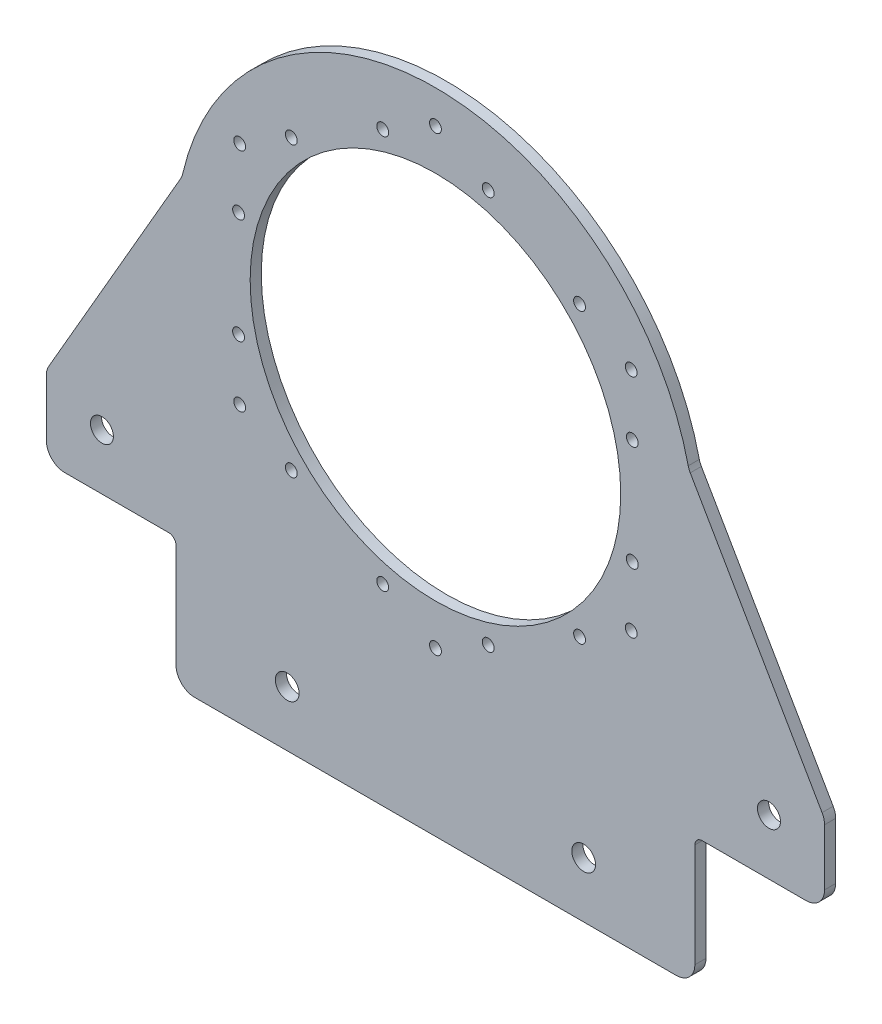
SolidWorks part; units mm, degrees
ref_plane "Front Plane" through (0, 0, 0) normal (0, 0, 1) x (1, 0, 0)
ref_plane "Top Plane" through (0, 0, 0) normal (0, 1, 0) x (1, 0, 0)
ref_plane "Right Plane" through (0, 0, 0) normal (1, 0, 0) x (0, 0, -1)
sketch "Sketch1" plane through (0, 0, 0) normal (0, 0, 1) x (1, 0, 0)
  line L0 (-70, 0) -> (-70, -70)
  line L2 (70, -70) -> (70, 0)
  line L7 (-70, -70) -> (70, -70)
  circle A0 centre (0, 0) radius 50
  arc A1 (70, 0) -> (-70, 0) centre (0, 0) ccw
  arc A2 (-70, 0) -> (0, -70) centre (0, 0) ccw construction
  arc A3 (0, -70) -> (70, 0) centre (0, 0) ccw construction
  dimension "D1" = 140
  dimension "D2" = 100
extrude "Boss-Extrude1" add sketch "Sketch1" along normal blind 3
sketch "Sketch2" plane through (0, 0, 3) normal (0, 0, 1) x (1, 0, 0)
  line L0 (0, 0) -> (0, 61) construction
  circle A0 centre (0, 61) radius 1.6
  circle A1 centre (52.8275, 30.5) radius 1.6
  circle A2 centre (52.8275, -30.5) radius 1.6
  circle A3 centre (0, -61) radius 1.6
  circle A4 centre (-52.8275, -30.5) radius 1.6
  circle A5 centre (-52.8275, 30.5) radius 1.6
  point P16 (0, 0)
  dimension "D1" = 3.2
  dimension "D2" = 61
  dimension "D3" = 6
extrude "Cut-Extrude1" cut sketch "Sketch2" against normal through all
sketch "Sketch3" plane through (0, 0, 3) normal (0, 0, 1) x (1, 0, 0)
  line L0 (0, 0) -> (14.235, 53.1259) construction
  line L1 (0, 0) -> (0, 26.2737) construction
  circle A0 centre (14.235, 53.1259) radius 1.6
  circle A1 centre (38.8909, 38.8909) radius 1.6
  circle A2 centre (53.1259, 14.235) radius 1.6
  circle A3 centre (53.1259, -14.235) radius 1.6
  circle A4 centre (38.8909, -38.8909) radius 1.6
  circle A5 centre (14.235, -53.1259) radius 1.6
  circle A6 centre (-14.235, -53.1259) radius 1.6
  circle A7 centre (-38.8909, -38.8909) radius 1.6
  circle A8 centre (-53.1259, -14.235) radius 1.6
  circle A9 centre (-53.1259, 14.235) radius 1.6
  circle A10 centre (-38.8909, 38.8909) radius 1.6
  circle A11 centre (-14.235, 53.1259) radius 1.6
  point P29 (0, 0)
  dimension "D1" = 3.2
  dimension "D2" = 55
  dimension "D3" = 15
  dimension "D4" = 12
extrude "Cut-Extrude2" cut sketch "Sketch3" against normal through all
sketch "Sketch4" plane through (0, 0, 3) normal (0, 0, 1) x (1, 0, 0)
  line L0 (-68.374, 15) -> (-105, -48.4381)
  line L1 (-105, -48.4381) -> (-105, -70)
  line L2 (-105, -70) -> (-70, -70)
  line L5 (0, 0) -> (0, -70) construction
  line L6 (-70, -70) -> (70, -70) construction
  line L8 (-70, -70) -> (-70, 0)
  line L9 (-90, -70) -> (-90, -55) construction
  line L10 (-40, -90) -> (40, -90) construction
  line L15 (-70, -70) -> (70, -70)
  line L16 (-70, -70) -> (-70, -105)
  line L17 (-70, -105) -> (70, -105)
  line L18 (70, -70) -> (70, -105)
  line L19 (105, -70) -> (70, -70)
  line L20 (105, -48.4381) -> (105, -70)
  line L21 (68.374, 15) -> (105, -48.4381)
  line L22 (70, -70) -> (70, 0)
  circle A0 centre (-40, -90) radius 3.2
  circle A1 centre (-90, -55) radius 3.1
  circle A2 centre (90, -55) radius 3.1
  circle A3 centre (40, -90) radius 3.2
  arc A4 (70, 0) -> (-70, 0) centre (0, 0) ccw construction
  arc A5 (70, 0) -> (68.374, 15) centre (0, 0) ccw
  arc A6 (-68.374, 15) -> (-70, 0) centre (0, 0) ccw
  arc A7 (68.374, 15) -> (70, 0) centre (0, 0) cw
  point P26 (0, -90)
  point P30 (-70, 11.9755)
  point P31 (-68.7758, 13.0342)
  point P32 (-70, 0)
  dimension "D4" = 6.2
  dimension "D5" = 6.4
  dimension "D1" = 30
  dimension "D2" = 35
  dimension "D3" = 15
  dimension "D6" = 80
  dimension "D7" = 15
  dimension "D8" = 35
  dimension "D9" = 15
  dimension "D10" = 15
extrude "Boss-Extrude2" add sketch "Sketch4" against normal up to surface (3 mm away)
chamfer "Chamfer1" [suppressed] distance 2.5 angle 45
thread "Thread1" [suppressed] pitch 0.7 start angle 0, offset 1, length 10, pitch 0.7, diameter 3.2
ref_plane "Plane1" through (-54.4275, -30.5, 4) normal (0, -1, 0) x (-1, 0, 0)
sketch "Thread Profile1" plane through (-54.4275, -30.5, 4) normal (0, -1, 0) x (-1, 0, 0)
  line L0 (0, 0) -> (0, 0.7) construction
  line L11 (0, 0) -> (0, 0.6125)
  line L12 (0, 0.6125) -> (-0.3789, 0.3937)
  line L13 (-0.3789, 0.3937) -> (-0.3789, 0.2187)
  line L15 (-0.3789, 0.2187) -> (0, 0)
  line L17 (-0.3789, 0.3062) -> (0, 0.3062) construction
  point P2 (0, 0)
  dimension "Pitch" = 0.7
  dimension "Profile_Angle" = 60
  dimension "Profile_Land" = 0.175
  dimension "Profile_Height" = 0.3789
pattern_circular "CirPattern1" [suppressed] count 6 over 360
fillet "Fillet1" radius 5 8 edges at (-68.374, 15, 1.5) (-105, -48.4381, 1.5) (-105, -70, 1.5) (-70, -105, 1.5) (70, -105, 1.5) (105, -70, 1.5) (105, -48.4381, 1.5) (68.374, 15, 1.5)
fillet "Fillet2" radius 2 2 edges at (70, -70, 1.5) (-70, -70, 1.5)
